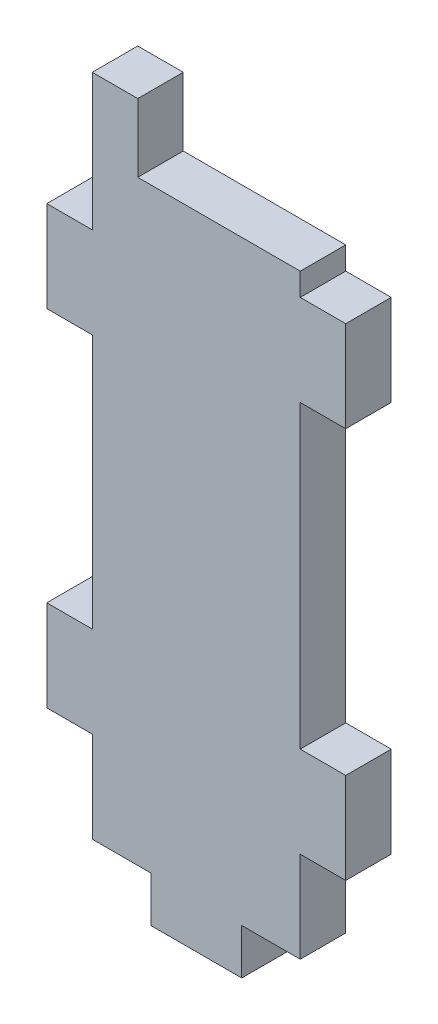
SolidWorks part; units mm, degrees
ref_plane "Plan de face" through (0, 0, 0) normal (0, 0, 1) x (1, 0, 0)
ref_plane "Plan de dessus" through (0, 0, 0) normal (0, 1, 0) x (1, 0, 0)
ref_plane "Plan de droite" through (0, 0, 0) normal (1, 0, 0) x (0, 0, -1)
sketch "Esquisse1" plane through (0, 0, 0) normal (0, 0, 1) x (1, 0, 0)
  line L1 (175.8171, 35.9774) -> (142.9571, 35.9774)
  line L2 (175.8171, 35.9774) -> (175.8171, -37.0226)
  line L3 (175.8171, -37.0226) -> (142.9571, -37.0226)
  line L4 (142.9571, 35.9774) -> (142.9571, -37.0226)
  dimension "D1" = 32.86
  dimension "D2" = 73
extrude "Boss.-Extru.1" add sketch "Esquisse1" along normal blind 5
sketch "Esquisse2" plane through (0, 0, 5) normal (0, 0, 1) x (1, 0, 0)
  line L0 (175.8171, 35.9774) -> (142.9571, 35.9774) construction
  line L1 (170.8171, 25.9774) -> (170.8171, 28.4774)
  line L2 (170.8171, 30.9774) -> (170.8171, 25.9774) construction
  line L3 (170.8171, 25.9774) -> (175.8171, 25.9774)
  line L4 (175.8171, 35.9774) -> (175.8171, 25.9774)
  line L5 (175.8171, -37.0226) -> (175.8171, 35.9774) construction
  line L6 (175.8171, 25.9774) -> (170.8171, 25.9774) construction
  line L7 (175.8171, -17.0226) -> (170.8171, -17.0226) construction
  line L8 (170.8171, 15.9774) -> (175.8171, 15.9774)
  line L9 (170.8171, 15.9774) -> (170.8171, -17.0226)
  line L10 (170.8171, -17.0226) -> (175.8171, -17.0226)
  line L11 (175.8171, 15.9774) -> (175.8171, -17.0226)
  line L12 (142.9571, 35.9774) -> (147.9571, 35.9774)
  line L13 (170.8171, -27.0226) -> (175.8171, -27.0226)
  line L14 (170.8171, -27.0226) -> (170.8171, -37.0226)
  line L15 (170.8171, -37.0226) -> (175.8171, -37.0226)
  line L16 (175.8171, -27.0226) -> (175.8171, -37.0226)
  line L17 (159.3871, 35.9774) -> (159.3871, -37.0226) construction
  line L18 (142.9571, -37.0226) -> (175.8171, -37.0226) construction
  line L19 (142.9571, -27.0226) -> (142.9571, -37.0226)
  line L20 (147.9571, -37.0226) -> (142.9571, -37.0226)
  line L21 (147.9571, -27.0226) -> (147.9571, -37.0226)
  line L22 (147.9571, -27.0226) -> (142.9571, -27.0226)
  line L23 (142.9571, 10.9774) -> (142.9571, -17.0226)
  line L24 (147.9571, -17.0226) -> (142.9571, -17.0226)
  line L25 (147.9571, 10.9774) -> (147.9571, -17.0226)
  line L26 (147.9571, 10.9774) -> (142.9571, 10.9774)
  line L27 (142.9571, 35.9774) -> (142.9571, 20.9774)
  line L28 (147.9571, 20.9774) -> (142.9571, 20.9774)
  line L29 (147.9571, 35.9774) -> (147.9571, 20.9774)
  line L30 (170.8171, 28.4774) -> (152.9571, 28.4774)
  line L31 (152.9571, 28.4774) -> (152.9571, 35.9774)
  line L32 (152.9571, 35.9774) -> (175.8171, 35.9774)
  dimension "D1" = 10
  dimension "D2" = 15
  dimension "D3" = 5
  dimension "D4" = 5
  dimension "D5" = 5
extrude "Enlèv. mat.-Extru.1" cut sketch "Esquisse2" against normal blind 5
sketch "Esquisse3" plane through (0, 0, 5) normal (0, 0, 1) x (1, 0, 0)
  line L0 (147.9571, -37.0226) -> (170.8171, -37.0226) construction
  line L1 (154.3871, -37.0226) -> (164.3871, -37.0226)
  line L2 (154.3871, -37.0226) -> (154.3871, -42.0226)
  line L3 (154.3871, -42.0226) -> (164.3871, -42.0226)
  line L4 (164.3871, -37.0226) -> (164.3871, -42.0226)
  line L5 (147.9571, -37.0226) -> (147.9571, -27.0226) construction
  dimension "D1" = 5
  dimension "D2" = 10
  dimension "D3" = 6.43
extrude "Boss.-Extru.2" add sketch "Esquisse3" against normal blind 5
